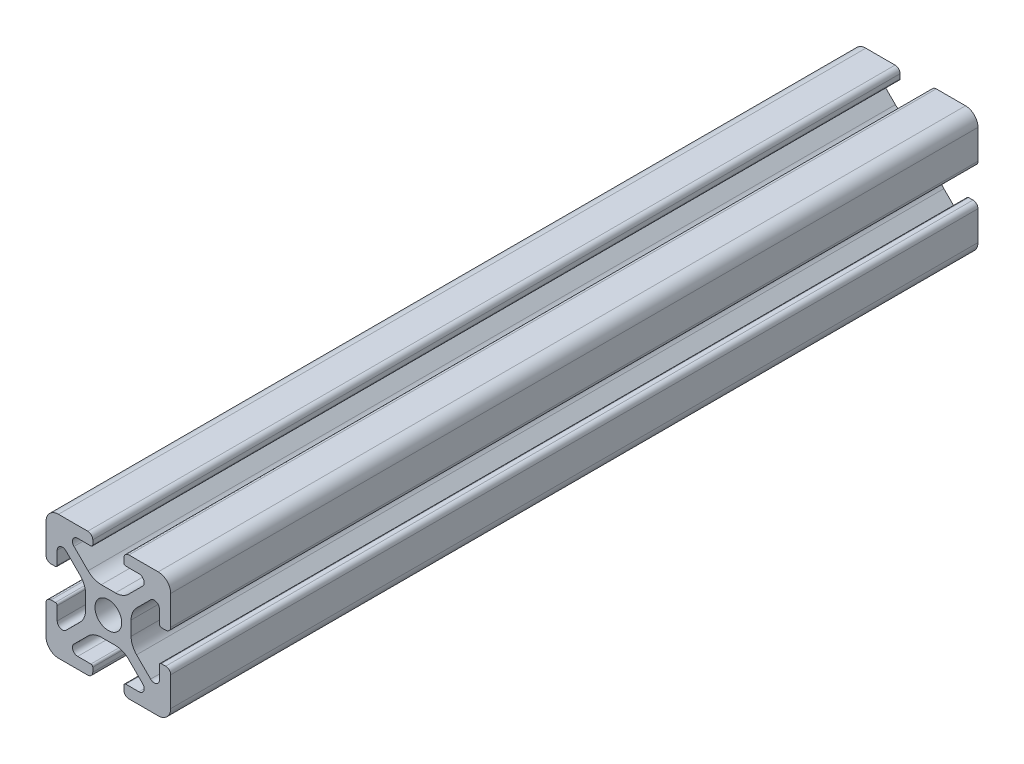
SolidWorks part; units mm, degrees
material "Alliage 1060"
ref_plane "Plan de face" through (0, 0, 0) normal (0, 0, 1) x (1, 0, 0)
ref_plane "Plan de dessus" through (0, 0, 0) normal (0, 1, 0) x (1, 0, 0)
ref_plane "Plan de droite" through (0, 0, 0) normal (1, 0, 0) x (0, 0, -1)
sketch "Esquisse1" plane through (0, 0, 0) normal (0, 0, 1) x (1, 0, 0)
  line L108 (-3.2559, 4.5287) -> (-5.5062, 6.779)
  line L109 (-4.9176, 8.2) -> (-2.8, 8.2)
  line L110 (-2.5, 8.5) -> (-2.5, 9.2)
  line L111 (-3.3, 10) -> (-8, 10)
  line L112 (-10, 8) -> (-10, 3.3)
  line L113 (-9.2, 2.5) -> (-8.5, 2.5)
  line L114 (-8.2, 2.8) -> (-8.2, 4.9176)
  line L115 (-6.779, 5.5062) -> (-4.5287, 3.2559)
  line L116 (-3.65, 1.1346) -> (-3.65, -1.1346)
  line L117 (-4.5287, -3.2559) -> (-6.779, -5.5062)
  line L118 (-8.2, -4.9176) -> (-8.2, -2.8)
  line L119 (-8.5, -2.5) -> (-9.2, -2.5)
  line L120 (-10, -3.3) -> (-10, -8)
  line L121 (-8, -10) -> (-3.3, -10)
  line L122 (-2.5, -9.2) -> (-2.5, -8.5)
  line L123 (-2.8, -8.2) -> (-4.9176, -8.2)
  line L124 (-5.5062, -6.779) -> (-3.2559, -4.5287)
  line L125 (-1.1346, -3.65) -> (1.1346, -3.65)
  line L126 (3.2559, -4.5287) -> (5.5062, -6.779)
  line L127 (4.9176, -8.2) -> (2.8, -8.2)
  line L128 (2.5, -8.5) -> (2.5, -9.2)
  line L129 (3.3, -10) -> (8, -10)
  line L130 (10, -8) -> (10, -3.3)
  line L131 (9.2, -2.5) -> (8.5, -2.5)
  line L132 (8.2, -2.8) -> (8.2, -4.9176)
  line L133 (6.779, -5.5062) -> (4.5287, -3.2559)
  line L134 (3.65, -1.1346) -> (3.65, 1.1346)
  line L135 (4.5287, 3.2559) -> (6.779, 5.5062)
  line L136 (8.2, 4.9176) -> (8.2, 2.8)
  line L137 (8.5, 2.5) -> (9.2, 2.5)
  line L138 (10, 3.3) -> (10, 8)
  line L139 (8, 10) -> (3.3, 10)
  line L140 (2.5, 9.2) -> (2.5, 8.5)
  line L141 (2.8, 8.2) -> (4.9176, 8.2)
  line L142 (5.5062, 6.779) -> (3.2559, 4.5287)
  line L143 (1.1346, 3.65) -> (-1.1346, 3.65)
  arc A42 (-2.15, 0) -> (2.15, 0) centre (0, 0) ccw
  arc A43 (2.15, 0) -> (-2.15, 0) centre (0, 0) ccw
  arc A108 (-4.9176, 8.2) -> (-5.5062, 6.779) centre (-4.9176, 7.3676) ccw
  arc A109 (-2.8, 8.2) -> (-2.5, 8.5) centre (-2.8, 8.5) ccw
  arc A110 (-2.5, 9.2) -> (-3.3, 10) centre (-3.3, 9.2) ccw
  arc A111 (-8, 10) -> (-10, 8) centre (-8, 8) ccw
  arc A112 (-10, 3.3) -> (-9.2, 2.5) centre (-9.2, 3.3) ccw
  arc A113 (-8.5, 2.5) -> (-8.2, 2.8) centre (-8.5, 2.8) ccw
  arc A114 (-6.779, 5.5062) -> (-8.2, 4.9176) centre (-7.3676, 4.9176) ccw
  arc A115 (-3.65, 1.1346) -> (-4.5287, 3.2559) centre (-6.65, 1.1346) ccw
  arc A116 (-4.5287, -3.2559) -> (-3.65, -1.1346) centre (-6.65, -1.1346) ccw
  arc A117 (-8.2, -4.9176) -> (-6.779, -5.5062) centre (-7.3676, -4.9176) ccw
  arc A118 (-8.2, -2.8) -> (-8.5, -2.5) centre (-8.5, -2.8) ccw
  arc A119 (-9.2, -2.5) -> (-10, -3.3) centre (-9.2, -3.3) ccw
  arc A120 (-10, -8) -> (-8, -10) centre (-8, -8) ccw
  arc A121 (-3.3, -10) -> (-2.5, -9.2) centre (-3.3, -9.2) ccw
  arc A122 (-2.5, -8.5) -> (-2.8, -8.2) centre (-2.8, -8.5) ccw
  arc A123 (-5.5062, -6.779) -> (-4.9176, -8.2) centre (-4.9176, -7.3676) ccw
  arc A124 (-1.1346, -3.65) -> (-3.2559, -4.5287) centre (-1.1346, -6.65) ccw
  arc A125 (3.2559, -4.5287) -> (1.1346, -3.65) centre (1.1346, -6.65) ccw
  arc A126 (4.9176, -8.2) -> (5.5062, -6.779) centre (4.9176, -7.3676) ccw
  arc A127 (2.8, -8.2) -> (2.5, -8.5) centre (2.8, -8.5) ccw
  arc A128 (2.5, -9.2) -> (3.3, -10) centre (3.3, -9.2) ccw
  arc A129 (8, -10) -> (10, -8) centre (8, -8) ccw
  arc A130 (10, -3.3) -> (9.2, -2.5) centre (9.2, -3.3) ccw
  arc A131 (8.5, -2.5) -> (8.2, -2.8) centre (8.5, -2.8) ccw
  arc A132 (6.779, -5.5062) -> (8.2, -4.9176) centre (7.3676, -4.9176) ccw
  arc A133 (3.65, -1.1346) -> (4.5287, -3.2559) centre (6.65, -1.1346) ccw
  arc A134 (4.5287, 3.2559) -> (3.65, 1.1346) centre (6.65, 1.1346) ccw
  arc A135 (8.2, 4.9176) -> (6.779, 5.5062) centre (7.3676, 4.9176) ccw
  arc A136 (8.2, 2.8) -> (8.5, 2.5) centre (8.5, 2.8) ccw
  arc A137 (9.2, 2.5) -> (10, 3.3) centre (9.2, 3.3) ccw
  arc A138 (10, 8) -> (8, 10) centre (8, 8) ccw
  arc A139 (3.3, 10) -> (2.5, 9.2) centre (3.3, 9.2) ccw
  arc A140 (2.5, 8.5) -> (2.8, 8.2) centre (2.8, 8.5) ccw
  arc A141 (5.5062, 6.779) -> (4.9176, 8.2) centre (4.9176, 7.3676) ccw
  arc A142 (1.1346, 3.65) -> (3.2559, 4.5287) centre (1.1346, 6.65) ccw
  arc A143 (-3.2559, 4.5287) -> (-1.1346, 3.65) centre (-1.1346, 6.65) ccw
extrude "Boss.-Extru.1" add sketch "Esquisse1" along normal blind 129.5
